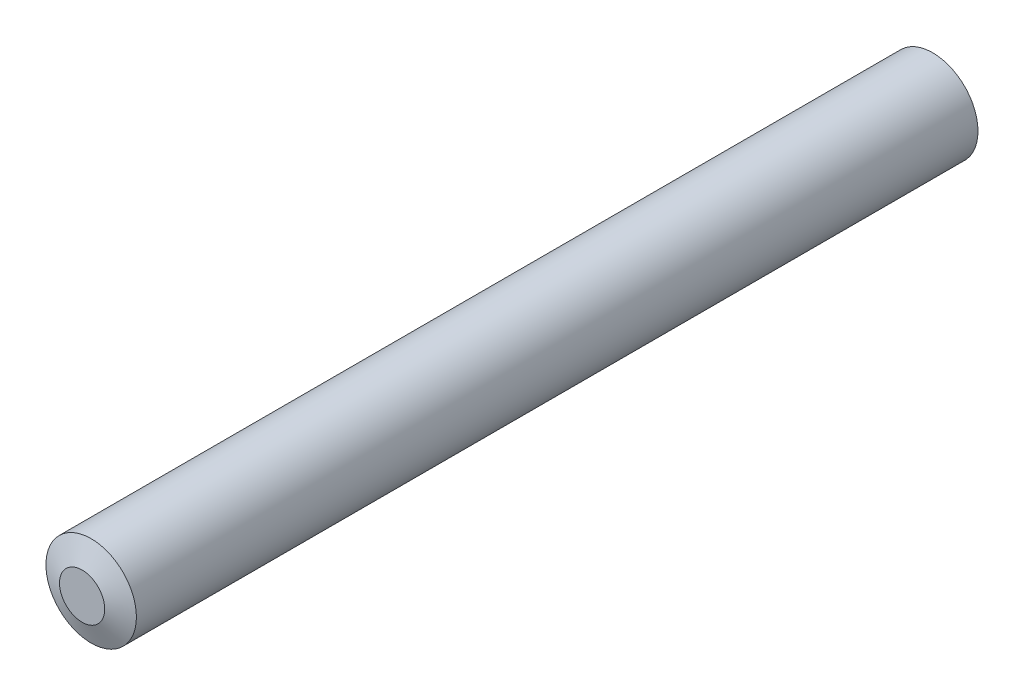
SolidWorks part; units mm, degrees
material "普通碳钢"
ref_plane "前视基准面" through (0, 0, 0) normal (0, 0, 1) x (1, 0, 0)
ref_plane "上视基准面" through (0, 0, 0) normal (0, 1, 0) x (1, 0, 0)
ref_plane "右视基准面" through (0, 0, 0) normal (1, 0, 0) x (0, 0, -1)
sketch "草图1" plane through (0, 0, 0) normal (0, 0, 1) x (1, 0, 0)
  circle A0 centre (0, 0) radius 2
  dimension "D1" = 4
extrude "拉伸1" add sketch "草图1" along normal mid plane 38
chamfer "倒角1" distance 0.4 distance2 1 1 edges at (2, 0, 19)
chamfer "倒角2" distance 1 distance2 0.4 1 edges at (2, 0, -19)
